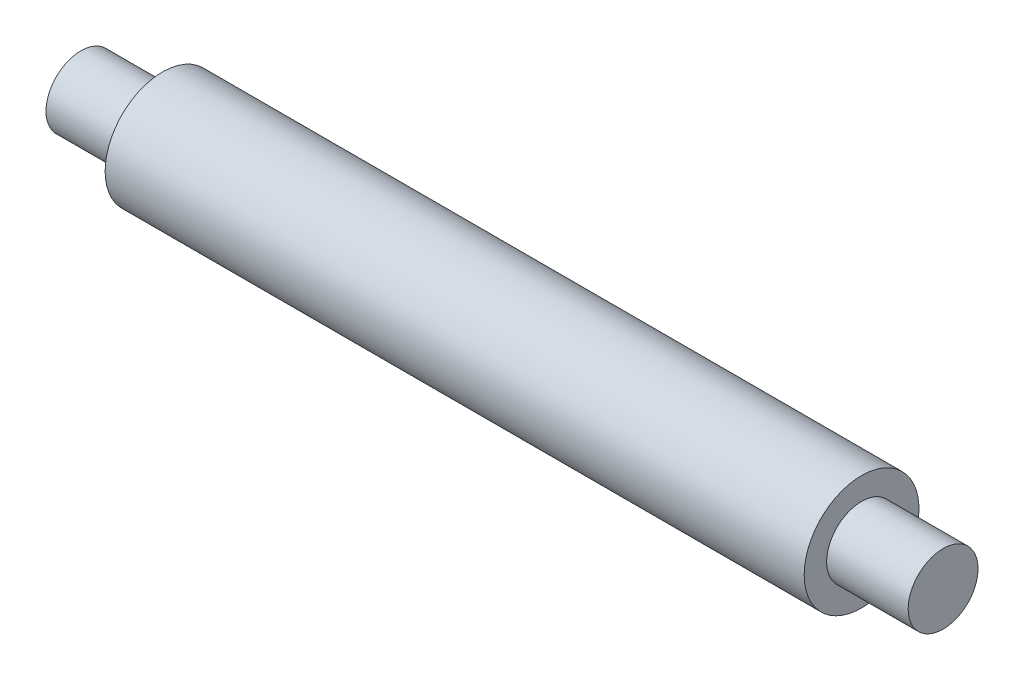
SolidWorks part; units mm, degrees
ref_plane "Front Plane" through (0, 0, 0) normal (0, 0, 1) x (1, 0, 0)
ref_plane "Top Plane" through (0, 0, 0) normal (0, 1, 0) x (1, 0, 0)
ref_plane "Right Plane" through (0, 0, 0) normal (1, 0, 0) x (0, 0, -1)
sketch "Sketch1" plane through (0, 0, 0) normal (0, 0, 1) x (1, 0, 0)
  line L0 (0, 0) -> (30, 0)
  line L1 (30, 0) -> (37, 0)
  line L2 (37, 0) -> (37, 1.5)
  line L3 (37, 1.5) -> (33.5, 1.5)
  line L4 (33.5, 1.5) -> (33.5, 2.4625)
  line L5 (33.5, 2.4625) -> (3.5, 2.4625)
  line L6 (3.5, 2.4625) -> (3.5, 1.5)
  line L7 (3.5, 1.5) -> (0, 1.5)
  line L8 (0, 1.5) -> (0, 0)
revolve "Revolve1" add sketch "Sketch1" angle 360 about L0
